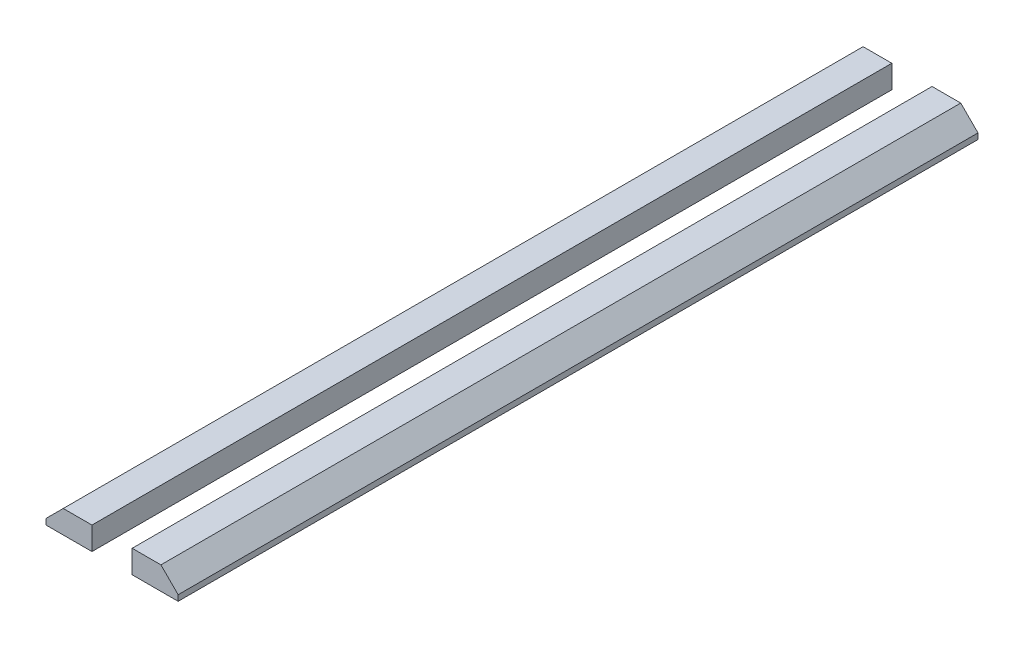
SolidWorks part; units mm, degrees
material "ABS"
ref_plane "Front Plane" through (0, 0, 0) normal (0, 0, 1) x (1, 0, 0)
ref_plane "Top Plane" through (0, 0, 0) normal (0, 1, 0) x (1, 0, 0)
ref_plane "Right Plane" through (0, 0, 0) normal (1, 0, 0) x (0, 0, -1)
sketch "Sketch1" plane through (0, 0, 0) normal (0, 0, 1) x (1, 0, 0)
  line L0 (-3.5, 0) -> (3.5, 0)
  line L1 (-3.5, 0) -> (-3.5, -4)
  line L2 (-3.5, -4) -> (-11.5, -4)
  line L3 (-11.5, -4) -> (-11.5, -3)
  line L5 (0, 0) -> (0, 1.8576) construction
  line L7 (11.5, -4) -> (11.5, -3)
  line L8 (3.5, -4) -> (11.5, -4)
  line L9 (3.5, 0) -> (3.5, -4)
  line L10 (-3.5, 0) -> (-8.5, 0)
  line L11 (-8.5, 0) -> (-11.5, -3)
  line L12 (3.5, 0) -> (8.5, 0)
  line L13 (8.5, 0) -> (11.5, -3)
  point P4 (0, 0)
extrude "Boss-Extrude1" add sketch "Sketch1" against normal up to surface (139.2174 mm away)
